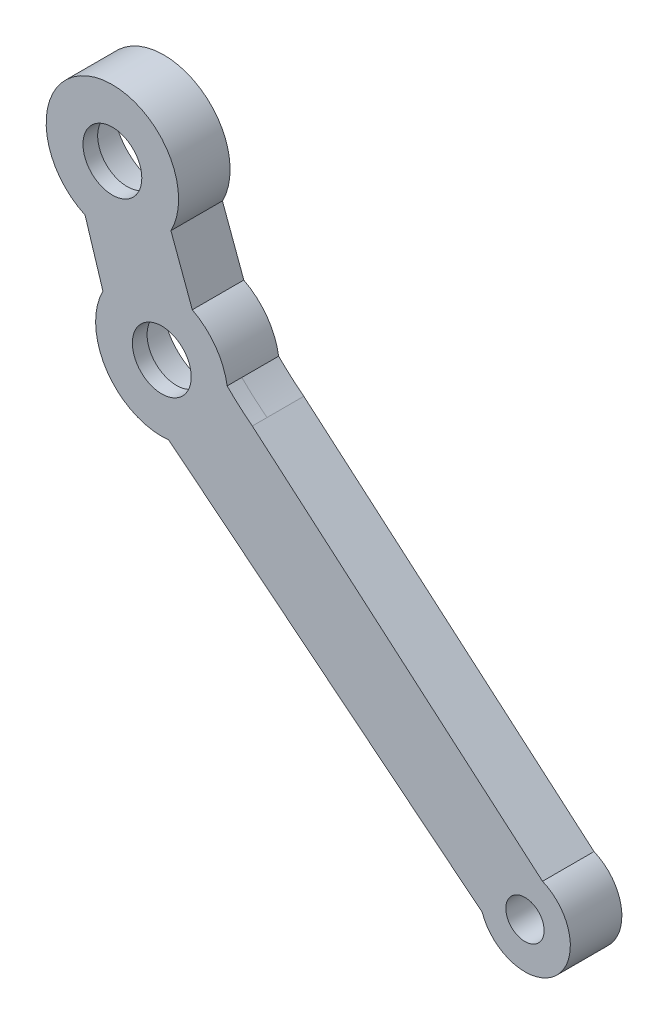
SolidWorks part; units mm, degrees
ref_plane "Front Plane" through (0, 0, 0) normal (0, 0, 1) x (1, 0, 0)
ref_plane "Top Plane" through (0, 0, 0) normal (0, 1, 0) x (1, 0, 0)
ref_plane "Right Plane" through (0, 0, 0) normal (1, 0, 0) x (0, 0, -1)
sketch "Sketch1" plane through (0, 0, 0) normal (0, 0, 1) x (1, 0, 0)
  line L4 (-169.858, 12.3281) -> (-127.2538, -21.9374)
  line L5 (-172.0822, 43.962) -> (-172.1127, 44.0448)
  line L6 (-177.675, 21.8061) -> (-177.6506, 21.7282)
  line L8 (-173.7115, 15.4274) -> (-172.7465, 14.6513)
  line L9 (-119.0478, -14.2184) -> (-158.4917, 19.6461)
  line L10 (-166.6455, 29.2483) -> (-169.5513, 37.1125)
  line L11 (-181.2224, 33.1197) -> (-178.7943, 25.3758)
  circle A2 centre (-170.7943, 21.2709) radius 6.9015
  arc A3 (-161.91, 22.6565) -> (-166.6455, 29.2483) centre (-170.7943, 21.2709) ccw
  arc A4 (-127.2538, -21.9374) -> (-119.0478, -14.2184) centre (-121.4321, -19.905) ccw
  arc A6 (-178.7943, 25.3758) -> (-169.858, 12.3281) centre (-170.7943, 21.2709) ccw
  circle A7 centre (-177.5085, 41.3176) radius 6.9
  arc A8 (-169.5513, 37.1125) -> (-181.2224, 33.1197) centre (-177.5085, 41.3176) ccw
  circle A9 centre (-121.4321, -19.905) radius 2.6
  parabola Q5 (-158.4917, 19.6461) -> (-161.91, 22.6565) focus (-150.532, 35.2115) apex (-163.1218, 23.941)
extrude "Boss-Extrude1" add sketch "Sketch1" along normal blind 5 contours L9 Q5 A3 L10 A8 L11 A6 L4 A4 A2 A7 A9
sketch "Sketch2" plane through (0, 0, 5) normal (0, 0, 1) x (1, 0, 0)
  line L4 (-119.0478, -14.2184) -> (-158.4917, 19.6461)
  line L5 (-166.6455, 29.2483) -> (-169.5513, 37.1125)
  line L6 (-181.2224, 33.1197) -> (-178.7943, 25.3758)
  line L7 (-169.858, 12.3281) -> (-127.2538, -21.9374)
  line L8 (-119.0478, -14.2184) -> (-158.4917, 19.6461)
  line L9 (-166.6455, 29.2483) -> (-169.5513, 37.1125)
  line L10 (-181.2224, 33.1197) -> (-178.7943, 25.3758)
  line L11 (-169.858, 12.3281) -> (-127.2538, -21.9374)
  circle A0 centre (-177.5085, 41.3176) radius 4
  circle A1 centre (-170.7943, 21.2709) radius 4
  circle A2 centre (-121.4321, -19.905) radius 2.6
  arc A4 (-161.91, 22.6565) -> (-166.6455, 29.2483) centre (-170.7943, 21.2709) ccw
  arc A5 (-169.5513, 37.1125) -> (-181.2224, 33.1197) centre (-177.5085, 41.3176) ccw
  arc A6 (-178.7943, 25.3758) -> (-169.858, 12.3281) centre (-170.7943, 21.2709) ccw
  arc A7 (-127.2538, -21.9374) -> (-119.0478, -14.2184) centre (-121.4321, -19.905) ccw
  arc A8 (-161.91, 22.6565) -> (-166.6455, 29.2483) centre (-170.7943, 21.2709) ccw
  arc A9 (-169.5513, 37.1125) -> (-181.2224, 33.1197) centre (-177.5085, 41.3176) ccw
  arc A10 (-178.7943, 25.3758) -> (-169.858, 12.3281) centre (-170.7943, 21.2709) ccw
  arc A11 (-127.2538, -21.9374) -> (-119.0478, -14.2184) centre (-121.4321, -19.905) ccw
  parabola Q1 (-158.4917, 19.6461) -> (-161.91, 22.6565) focus (-150.532, 35.2115) apex (-163.1218, 23.941)
  parabola Q2 (-158.4917, 19.6461) -> (-161.91, 22.6565) focus (-150.532, 35.2115) apex (-163.1218, 23.941)
  dimension "D2" = 8
  dimension "D3" = 8
  dimension "D1" = 0
extrude "Boss-Extrude2" add sketch "Sketch2" along normal blind 2
